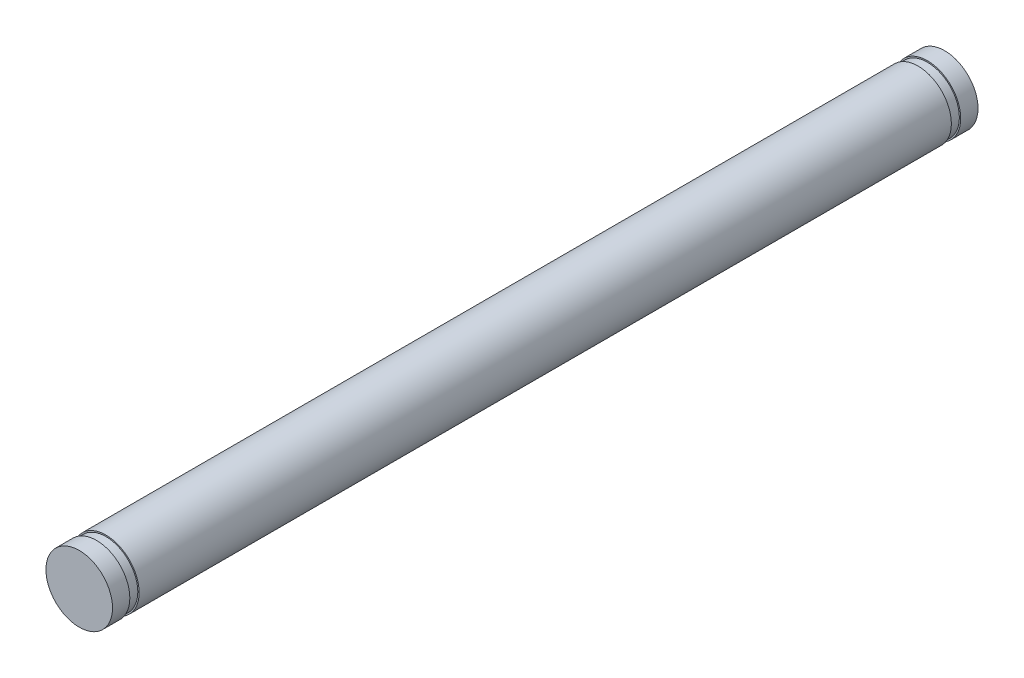
SolidWorks part; units mm, degrees
ref_plane "Płaszczyzna przednia" through (0, 0, 0) normal (0, 0, 1) x (1, 0, 0)
ref_plane "Płaszczyzna górna" through (0, 0, 0) normal (0, 1, 0) x (1, 0, 0)
ref_plane "Płaszczyzna prawa" through (0, 0, 0) normal (1, 0, 0) x (0, 0, -1)
sketch "Szkic1" plane through (0, 0, 0) normal (1, 0, 0) x (0, 0, -1)
  line L0 (-31.2, -2.5) -> (-31.2, -2.4)
  line L1 (-32.5, 0) -> (32.5, 0)
  line L2 (-32.5, 0) -> (-32.5, -2.5)
  line L3 (-32.5, -2.5) -> (-31.2, -2.5)
  line L4 (32.5, 0) -> (32.5, -2.5)
  line L5 (-31.2, -2.4) -> (-30.5, -2.4)
  line L6 (-30.5, -2.4) -> (-30.5, -2.5)
  line L7 (0, 0) -> (0, -12.913) construction
  line L8 (31.2, -2.5) -> (31.2, -2.4)
  line L9 (31.2, -2.4) -> (30.5, -2.4)
  line L10 (30.5, -2.4) -> (30.5, -2.5)
  line L11 (31.2, -2.5) -> (32.5, -2.5)
  line L12 (-30.5, -2.5) -> (30.5, -2.5)
  point P11 (0, 0)
  dimension "D1" = 65
  dimension "D2" = 2.5
  dimension "D3" = 0.7
  dimension "D4" = 0.1
  dimension "D5" = 61
revolve "Obrót1" add sketch "Szkic1" angle 360 about L1
